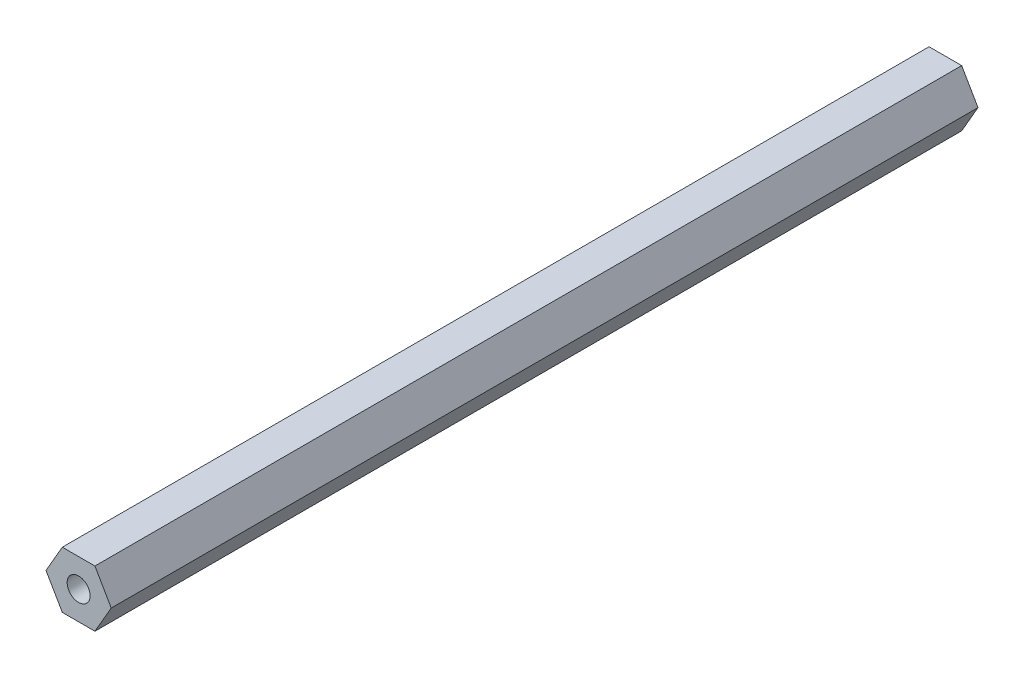
SolidWorks part; units mm, degrees
ref_plane "Front Plane" through (0, 0, 0) normal (0, 0, 1) x (1, 0, 0)
ref_plane "Top Plane" through (0, 0, 0) normal (0, 1, 0) x (1, 0, 0)
ref_plane "Right Plane" through (0, 0, 0) normal (1, 0, 0) x (0, 0, -1)
sketch "Sketch1" plane through (0, 0, 0) normal (0, 0, 1) x (1, 0, 0)
  line L1 (7.3323, 0) -> (3.6662, 6.35)
  line L2 (3.6662, 6.35) -> (-3.6662, 6.35)
  line L3 (-3.6662, 6.35) -> (-7.3323, 0)
  line L4 (-7.3323, 0) -> (-3.6662, -6.35)
  line L5 (-3.6662, -6.35) -> (3.6662, -6.35)
  line L6 (3.6662, -6.35) -> (7.3323, 0)
  circle A0 centre (0, 0) radius 6.35 construction
  circle A1 centre (0, 0) radius 2.5797
  dimension "D1" = 12.7
  dimension "D2" = 5.1594
extrude "Boss-Extrude1" add sketch "Sketch1" along normal blind 194.8244
